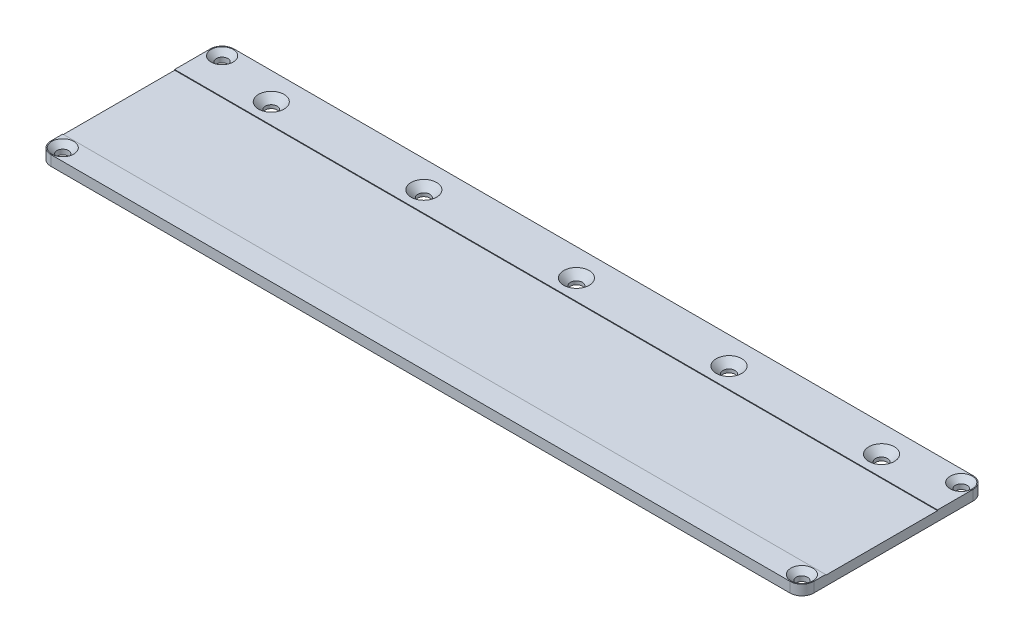
SolidWorks part; units mm, degrees
ref_plane "Front Plane" through (0, 0, 0) normal (0, 0, 1) x (1, 0, 0)
ref_plane "Top Plane" through (0, 0, 0) normal (0, 1, 0) x (1, 0, 0)
ref_plane "Right Plane" through (0, 0, 0) normal (1, 0, 0) x (0, 0, -1)
sketch "Sketch1" plane through (0, 0, 0) normal (0, 1, 0) x (1, 0, 0)
  line L0 (-112.5, 15.5) -> (112.5, 15.5) construction
  line L1 (-112.5, -23.5) -> (112.5, -23.5) construction
  line L2 (-112.5, -23.5) -> (-112.5, 23.5)
  line L3 (-112.5, 23.5) -> (112.5, 23.5)
  line L4 (112.5, -23.5) -> (112.5, 23.5)
  line L5 (-112.5, -23.5) -> (112.5, 23.5) construction
  line L6 (-112.5, 23.5) -> (112.5, -23.5) construction
  line L7 (-112.5, -23.5) -> (112.5, -23.5) construction
  line L8 (-112.5, -23.5) -> (-112.5, 9.5)
  line L9 (-112.5, 9.5) -> (112.5, 9.5) construction
  line L10 (112.5, -23.5) -> (112.5, 9.5)
  line L12 (-112.5, -23.5) -> (112.5, -23.5)
  line L13 (-112.5, -23.5) -> (-112.5, -30.5)
  line L14 (-112.5, -30.5) -> (112.5, -30.5)
  line L15 (112.5, -23.5) -> (112.5, -30.5)
  point P0 (0, 0)
  point P10 (0, 9.5)
  point P16 (0, 0)
  dimension "D1" = 112.5
  dimension "D3" = 33
  dimension "D4" = 225
  dimension "D5" = 6
  dimension "D2" = 8
  dimension "D6" = 7
extrude "Boss-Extrude1" add sketch "Sketch1" along normal blind 3 contours L1 L4 L3 L2 | L13 L12 L15 L14
sketch "Sketch2" plane through (0, 3, 0) normal (0, 1, 0) x (1, 0, 0)
  line L0 (-90, -7) -> (-45, -7) construction
  line L1 (-45, -7) -> (0, -7) construction
  line L2 (0, -7) -> (45, -7) construction
  line L3 (45, -7) -> (90, -7) construction
  line L4 (112.5, -30.5) -> (112.5, 23.5) construction
  line L6 (-112.5, -23.5) -> (112.5, -23.5)
  line L7 (-112.5, -23.5) -> (-112.5, 9.5)
  line L8 (-112.5, 9.5) -> (112.5, 9.5)
  line L9 (112.5, -23.5) -> (112.5, 9.5)
  line L10 (-112.5, -23.5) -> (112.5, 9.5) construction
  line L11 (-112.5, 9.5) -> (112.5, -23.5) construction
  circle A0 centre (-90, -7) radius 15
  circle A1 centre (-45, -7) radius 15
  circle A2 centre (0, -7) radius 15
  circle A3 centre (45, -7) radius 15
  circle A4 centre (90, -7) radius 15
  point P10 (-112.5, -17.5481)
  point P11 (112.5, -21.1973)
  point P17 (112.5, -22.5)
  point P19 (0, 0)
  point P20 (112.5, -22.5)
  line M11 (112.5, -30.5) -> (112.5, 23.5)
  line M13 (-112.5, 23.5) -> (-112.5, -30.5)
  dimension "D1" = 30
  dimension "D2" = 45
  dimension "D3" = 33
  dimension "D4" = 23.5
sketch "Sketch3" plane through (0, 3, 0) normal (0, 1, 0) x (1, 0, 0)
  line L0 (-90, 15.5) -> (-45, 15.5) construction
  line L1 (-45, 15.5) -> (0, 15.5) construction
  line L2 (0, 15.5) -> (45, 15.5) construction
  line L3 (45, 15.5) -> (90, 15.5) construction
  line L4 (-112.5, 23.5) -> (112.5, 23.5) construction
  line L6 (-1.25, 14.25) -> (1.25, 14.25) construction
  line L7 (-1.25, 14.25) -> (-1.25, 16.75) construction
  line L8 (-1.25, 16.75) -> (1.25, 16.75) construction
  line L9 (1.25, 14.25) -> (1.25, 16.75) construction
  line L10 (-1.25, 14.25) -> (1.25, 16.75) construction
  line L11 (-1.25, 16.75) -> (1.25, 14.25) construction
  circle A0 centre (0, 15.5) radius 1.7678
  circle A1 centre (45, 15.5) radius 1.7678
  circle A2 centre (90, 15.5) radius 1.7678
  circle A3 centre (-45, 15.5) radius 1.7678
  circle A4 centre (-90, 15.5) radius 1.7678
  dimension "D2" = 8
  dimension "D1" = 45
  dimension "D3" = 2.5
extrude "Cut-Extrude1" cut sketch "Sketch3" against normal through all
chamfer "Chamfer2" distance 2 angle 45 5 edges at (90, 3, -13.7322) (45, 3, -13.7322) (0, 3, -13.7322) (-45, 3, -13.7322) (-90, 3, -13.7322)
extrude "Cut-Extrude2" cut sketch "Sketch2" against normal blind 0.2 contours L8 L6 A4 A3 A2 A1 A0 M13 M11 | A0 | A1 | A2 | A3 | A4
fillet "Fillet1" radius 3.5 4 edges at (-112.5, 1.5, -23.5) (112.5, 1.5, 30.5) (-112.5, 1.5, 30.5) (112.5, 1.5, -23.5)
sketch "Sketch6" plane through (0, 3, 0) normal (0, 1, 0) x (1, 0, 0)
  line L0 (112.5, -23.5) -> (112.5, 9.5) construction
  line L1 (-109, 20) -> (109, 20) construction
  line L2 (-109, 20) -> (-109, -27) construction
  line L3 (-109, -27) -> (109, -27) construction
  line L4 (109, 20) -> (109, -27) construction
  line L5 (-112.5, -23.5) -> (-112.5, 9.5) construction
  line L6 (-109, -30.5) -> (109, -30.5) construction
  line L7 (-109, 23.5) -> (109, 23.5) construction
  dimension "D1" = 3.5
  dimension "D2" = 3.5
  dimension "D3" = 3.5
  dimension "D4" = 3.5
hole_wizard "CSK for M3 Countersunk Flat Head Screw1" positions "Sketch4" profile "Sketch5" countersink size "M3" standard "ISO" end condition through all
sketch "Sketch4" plane through (0, 3, 0) normal (0, 1, 0) x (1, 0, 0)
  point P3 (109, 20)
  point P6 (109, -27)
  point P9 (-109, -27)
  point P12 (-109, 20)
  point P16 (0, 0)
sketch "Sketch5" plane through (109, 3, -20) normal (1, 0, 0) x (0, 0, 1)
  line L0 (0, 0) -> (0, 3)
  line L1 (0, 3) -> (1.7, 3)
  line L2 (1.7, 3) -> (1.7, 1.55)
  line L3 (1.7, 1.55) -> (3.25, 0)
  line L5 (3.25, 0) -> (0, 0)
  line L6 (-1.7, 1.55) -> (-3.25, 0) construction
  line L11 (0, -6.35) -> (0, 107.95) construction
  dimension "Thru Hole Dia." = 3.4
  dimension "Thru Hole Depth" = 3
  dimension "Near C'Sink Dia." = 6.5
  dimension "Near C'Sink Angle" = 90
equation "\"Target White\"= 550mm"
equation "\"Scaled Distance\"= 1.5"
equation "\"Scale Factor\"= 25 / \"Scaled Distance\"'Scaled "
equation "\"Scaled White\"= \"Target White\" / \"Scale Factor\""
equation "\"Scaled Spacing\"= 750 / \"Scale Factor\""
equation "\"D4@Sketch1\"=\"Scaled Spacing\"*5"
equation "\"D1@Sketch3\"=\"Scaled Spacing\""
